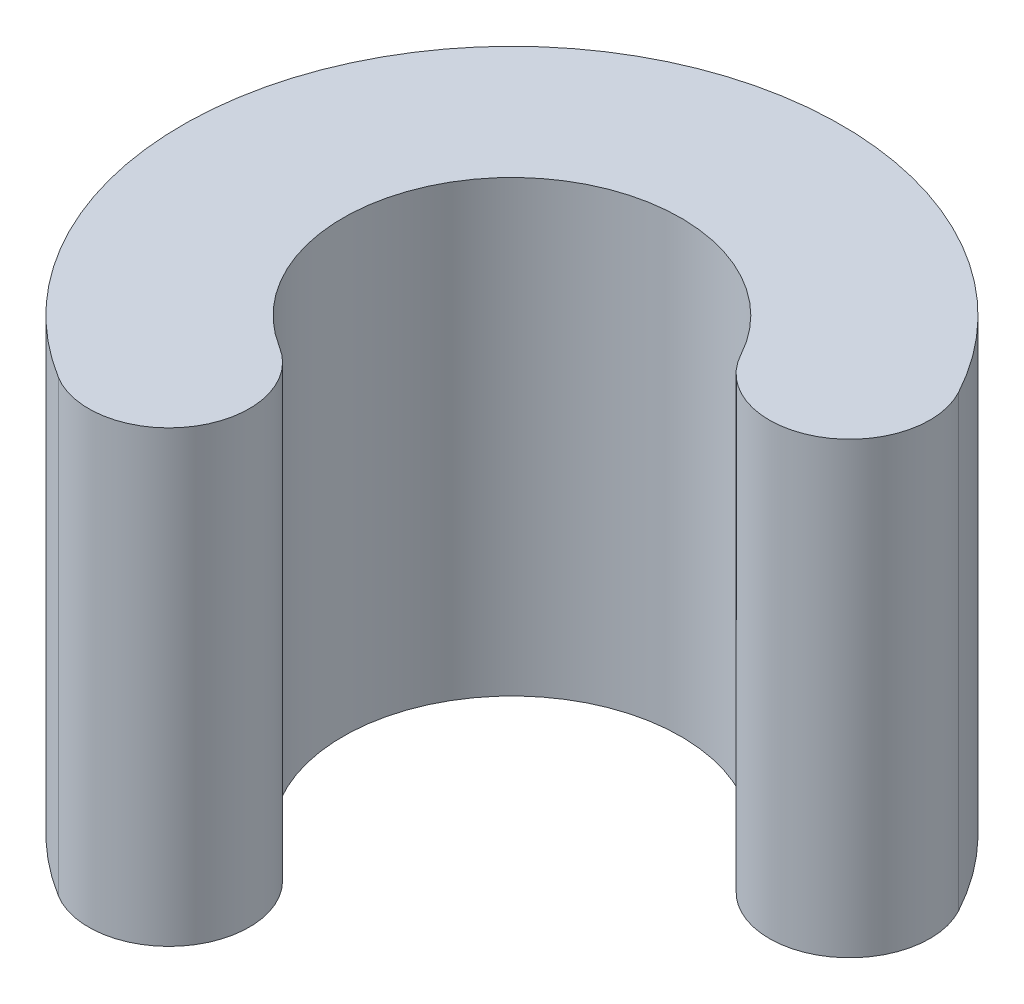
SolidWorks part; units mm, degrees
ref_plane "Piano frontale" through (0, 0, 0) normal (0, 0, 1) x (1, 0, 0)
ref_plane "Piano superiore" through (0, 0, 0) normal (0, 1, 0) x (1, 0, 0)
ref_plane "Piano destro" through (0, 0, 0) normal (1, 0, 0) x (0, 0, -1)
sketch "Schizzo1" plane through (0, 0, 0) normal (0, 1, 0) x (1, 0, 0)
  line L2 (-3.1753, -5.1498) -> (0, 0) construction
  line L3 (0, 0) -> (5.3248, 2.8722) construction
  arc A0 (3.6085, 1.9464) -> (-2.1519, -3.4899) centre (0, 0) ccw
  arc A1 (7.041, 3.7979) -> (-3.3093, -7.2834) centre (0, 0) ccw
  circle A2 centre (5.3248, 2.8722) radius 1.95
  circle A3 centre (-3.1753, -5.1498) radius 1.95
  point P10 (0, 0)
  dimension "D1" = 150
  dimension "8.3" = 8.2
  dimension "D2" = 16
extrude "Estrusione-Estrusione1" add sketch "Schizzo1" along normal blind 10.9
